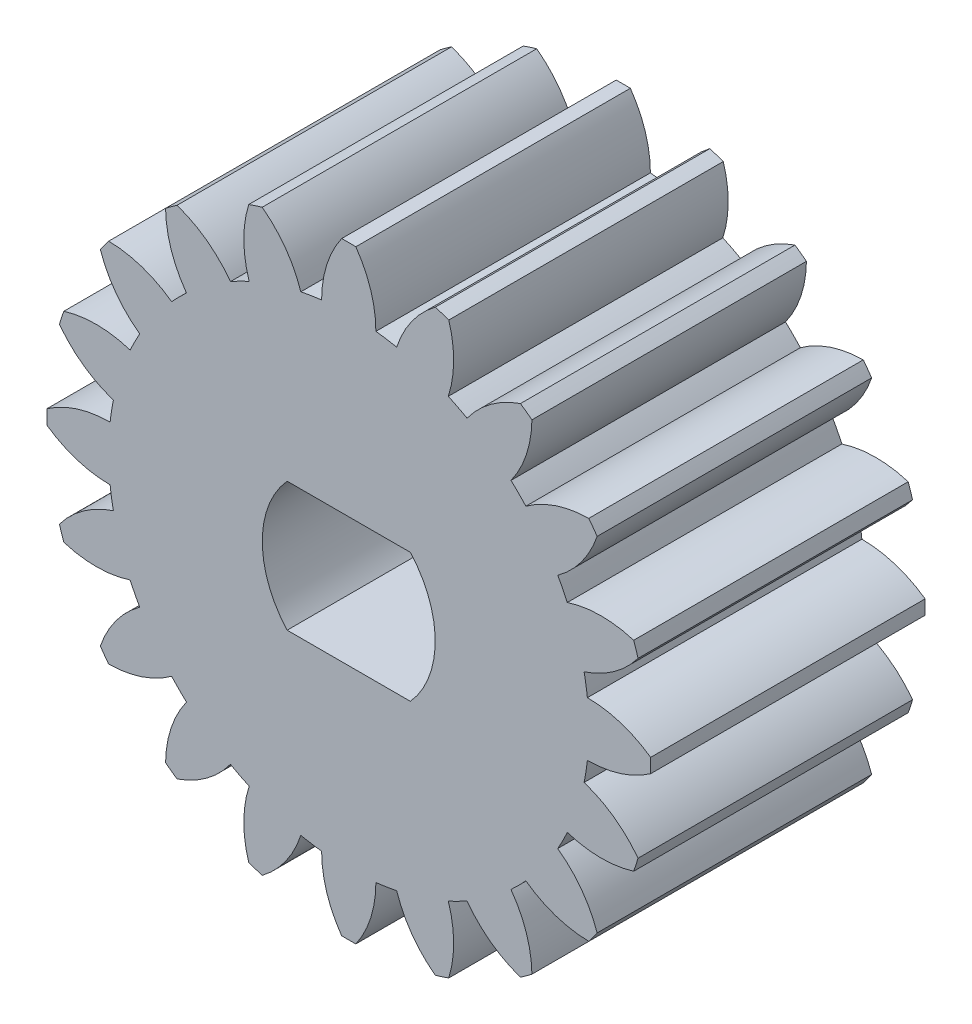
SolidWorks part; units mm, degrees
ref_plane "Front Plane" through (0, 0, 0) normal (0, 0, 1) x (1, 0, 0)
ref_plane "Top Plane" through (0, 0, 0) normal (0, 1, 0) x (1, 0, 0)
ref_plane "Right Plane" through (0, 0, 0) normal (1, 0, 0) x (0, 0, -1)
sketch "Sketch1" plane through (0, 0, 0) normal (0, 0, 1) x (1, 0, 0)
  line L0 (-0.2585, 10.997) -> (0.2585, 10.997) construction
  line L1 (0.9887, 8.693) -> (-0.9887, 8.693) construction
  line L4 (-2.0117, 1.85) -> (2.0117, 1.85)
  line L5 (2.0117, -1.85) -> (-2.0117, -1.85)
  line L6 (0, 1.85) -> (0, -1.85) construction
  line L7 (-2.2437, 2.35) -> (2.2437, 2.35)
  line L8 (2.2437, -2.35) -> (-2.2437, -2.35)
  circle A0 centre (0, 0) radius 11
  circle A1 centre (0, 0) radius 8.749
  arc A2 (-0.2585, 10.997) -> (-0.9887, 8.693) centre (3.0113, 8.693) ccw
  arc A3 (0.2585, 10.997) -> (0.9887, 8.693) centre (-3.0113, 8.693) cw
  arc A4 (3.6441, 10.3789) -> (3.6266, 7.962) centre (-0.1776, 9.198) cw
  arc A5 (3.1524, 10.5386) -> (1.746, 8.573) centre (5.5502, 7.337) ccw
  arc A6 (6.673, 8.7448) -> (5.9095, 6.4516) centre (2.6734, 8.8027) cw
  arc A7 (6.2547, 9.0487) -> (4.3097, 7.6139) centre (7.5458, 5.2628) ccw
  arc A8 (9.0487, 6.2547) -> (7.6139, 4.3097) centre (5.2628, 7.5458) cw
  arc A9 (8.7448, 6.673) -> (6.4516, 5.9095) centre (8.8027, 2.6734) ccw
  arc A10 (10.5386, 3.1524) -> (8.573, 1.746) centre (7.337, 5.5502) cw
  arc A11 (10.3789, 3.6441) -> (7.962, 3.6266) centre (9.198, -0.1776) ccw
  arc A12 (10.997, -0.2585) -> (8.693, -0.9887) centre (8.693, 3.0113) cw
  arc A13 (10.997, 0.2585) -> (8.693, 0.9887) centre (8.693, -3.0113) ccw
  arc A14 (10.3789, -3.6441) -> (7.962, -3.6266) centre (9.198, 0.1776) cw
  arc A15 (10.5386, -3.1524) -> (8.573, -1.746) centre (7.337, -5.5502) ccw
  arc A16 (8.7448, -6.673) -> (6.4516, -5.9095) centre (8.8027, -2.6734) cw
  arc A17 (9.0487, -6.2547) -> (7.6139, -4.3097) centre (5.2628, -7.5458) ccw
  arc A18 (6.2547, -9.0487) -> (4.3097, -7.6139) centre (7.5458, -5.2628) cw
  arc A19 (6.673, -8.7448) -> (5.9095, -6.4516) centre (2.6734, -8.8027) ccw
  arc A20 (3.1524, -10.5386) -> (1.746, -8.573) centre (5.5502, -7.337) cw
  arc A21 (3.6441, -10.3789) -> (3.6266, -7.962) centre (-0.1776, -9.198) ccw
  arc A22 (-0.2585, -10.997) -> (-0.9887, -8.693) centre (3.0113, -8.693) cw
  arc A23 (0.2585, -10.997) -> (0.9887, -8.693) centre (-3.0113, -8.693) ccw
  arc A24 (-3.6441, -10.3789) -> (-3.6266, -7.962) centre (0.1776, -9.198) cw
  arc A25 (-3.1524, -10.5386) -> (-1.746, -8.573) centre (-5.5502, -7.337) ccw
  arc A26 (-6.673, -8.7448) -> (-5.9095, -6.4516) centre (-2.6734, -8.8027) cw
  arc A27 (-6.2547, -9.0487) -> (-4.3097, -7.6139) centre (-7.5458, -5.2628) ccw
  arc A28 (-9.0487, -6.2547) -> (-7.6139, -4.3097) centre (-5.2628, -7.5458) cw
  arc A29 (-8.7448, -6.673) -> (-6.4516, -5.9095) centre (-8.8027, -2.6734) ccw
  arc A30 (-10.5386, -3.1524) -> (-8.573, -1.746) centre (-7.337, -5.5502) cw
  arc A31 (-10.3789, -3.6441) -> (-7.962, -3.6266) centre (-9.198, 0.1776) ccw
  arc A32 (-10.997, 0.2585) -> (-8.693, 0.9887) centre (-8.693, -3.0113) cw
  arc A33 (-10.997, -0.2585) -> (-8.693, -0.9887) centre (-8.693, 3.0113) ccw
  arc A34 (-10.3789, 3.6441) -> (-7.962, 3.6266) centre (-9.198, -0.1776) cw
  arc A35 (-10.5386, 3.1524) -> (-8.573, 1.746) centre (-7.337, 5.5502) ccw
  arc A36 (-8.7448, 6.673) -> (-6.4516, 5.9095) centre (-8.8027, 2.6734) cw
  arc A37 (-9.0487, 6.2547) -> (-7.6139, 4.3097) centre (-5.2628, 7.5458) ccw
  arc A38 (-6.2547, 9.0487) -> (-4.3097, 7.6139) centre (-7.5458, 5.2628) cw
  arc A39 (-6.673, 8.7448) -> (-5.9095, 6.4516) centre (-2.6734, 8.8027) ccw
  arc A40 (-3.1524, 10.5386) -> (-1.746, 8.573) centre (-5.5502, 7.337) cw
  arc A41 (-3.6441, 10.3789) -> (-3.6266, 7.962) centre (0.1776, 9.198) ccw
  arc A45 (-2.0117, 1.85) -> (-2.0117, -1.85) centre (0.35, 0) ccw
  arc A46 (2.0117, 1.85) -> (2.0117, -1.85) centre (-0.35, 0) cw
  arc A47 (2.2437, 2.35) -> (2.2437, -2.35) centre (-0.35, 0) cw
  arc A48 (-2.2437, 2.35) -> (-2.2437, -2.35) centre (0.35, 0) ccw
  point P128 (0, -1.85)
  point P129 (0, 1.85)
  point P132 (0, 0)
  point P135 (-2.65, 0)
  point P136 (2.65, 0)
  dimension "D1" = 22
  dimension "D2" = 3.7
  dimension "D3" = 4
  dimension "D4" = 0.517
  dimension "D9" = 3
  dimension "D10" = 1.9774
  dimension "D6" = 0.7572
  dimension "D7" = 2.93
  dimension "D8" = 5.3
  dimension "D11" = 0.5
  dimension "D5" = 20
extrude "Boss-Extrude1" add sketch "Sketch1" along normal blind 10 contours A1 L4 A46 L5 A45 | A0 A37 A1 A36 | A0 A39 A1 A38 | A0 A41 A1 A40 | A3 A0 A2 A1 | A0 A5 A1 A4 | A0 A7 A1 A6 | A0 A9 A1 A8 | A0 A11 A1 A10 | A0 A13 A1 A12 | A0 A15 A1 A14 | A0 A17 A1 A16 | A0 A19 A1 A18 | A0 A21 A1 A20 | A0 A23 A1 A22 | A0 A25 A1 A24 | A0 A27 A1 A26 | A0 A29 A1 A28 | A0 A31 A1 A30 | A0 A33 A1 A32 | A0 A35 A1 A34
